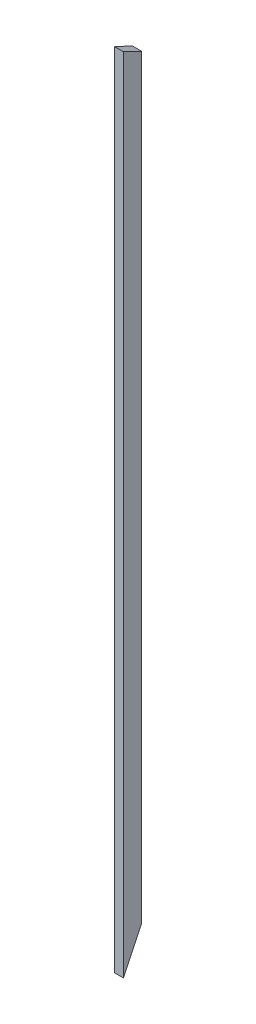
SolidWorks part; units mm, degrees
ref_plane "Спереди" through (0, 0, 0) normal (0, 0, 1) x (1, 0, 0)
ref_plane "Сверху" through (0, 0, 0) normal (0, 1, 0) x (1, 0, 0)
ref_plane "Справа" through (0, 0, 0) normal (1, 0, 0) x (0, 0, -1)
other "Configuration Table"
sketch "Эскиз1" plane through (0, 0, 0) normal (0, 1, 0) x (1, 0, 0)
  line L1 (12.5, 25) -> (-12.5, 25)
  line L2 (12.5, 25) -> (12.5, -25)
  line L3 (12.5, -25) -> (-12.5, -25)
  line L4 (-12.5, 25) -> (-12.5, -25)
  line L5 (12.5, 25) -> (-12.5, -25) construction
  line L6 (12.5, -25) -> (-12.5, 25) construction
  point P0 (0, 0)
extrude "Бобышка-Вытянуть1" add sketch "Эскиз1" along normal blind 2214.159
sketch "Эскиз3" plane through (-12.5, 0, 0) normal (-1, 0, 0) x (0, 0, 1)
  line L0 (25, 0) -> (-25, 105.258)
  line L1 (-25, 2214.159) -> (-25, 0) construction
  line L2 (-25, 105.258) -> (-25, 0)
  line L3 (-25, 0) -> (25, 0)
extrude "Вырез-Вытянуть2" cut sketch "Эскиз3" against normal blind 50
sketch "Эскиз4" plane through (-12.5, 0, 0) normal (-1, 0, 0) x (0, 0, 1)
  line L0 (25, 2214.159) -> (-25, 2190.4182)
  line L1 (-25, 2214.159) -> (-25, 105.258) construction
  line L2 (-25, 2190.4182) -> (-25, 2214.159)
  line L3 (-25, 2214.159) -> (25, 2214.159)
extrude "Вырез-Вытянуть3" cut sketch "Эскиз4" against normal blind 50
